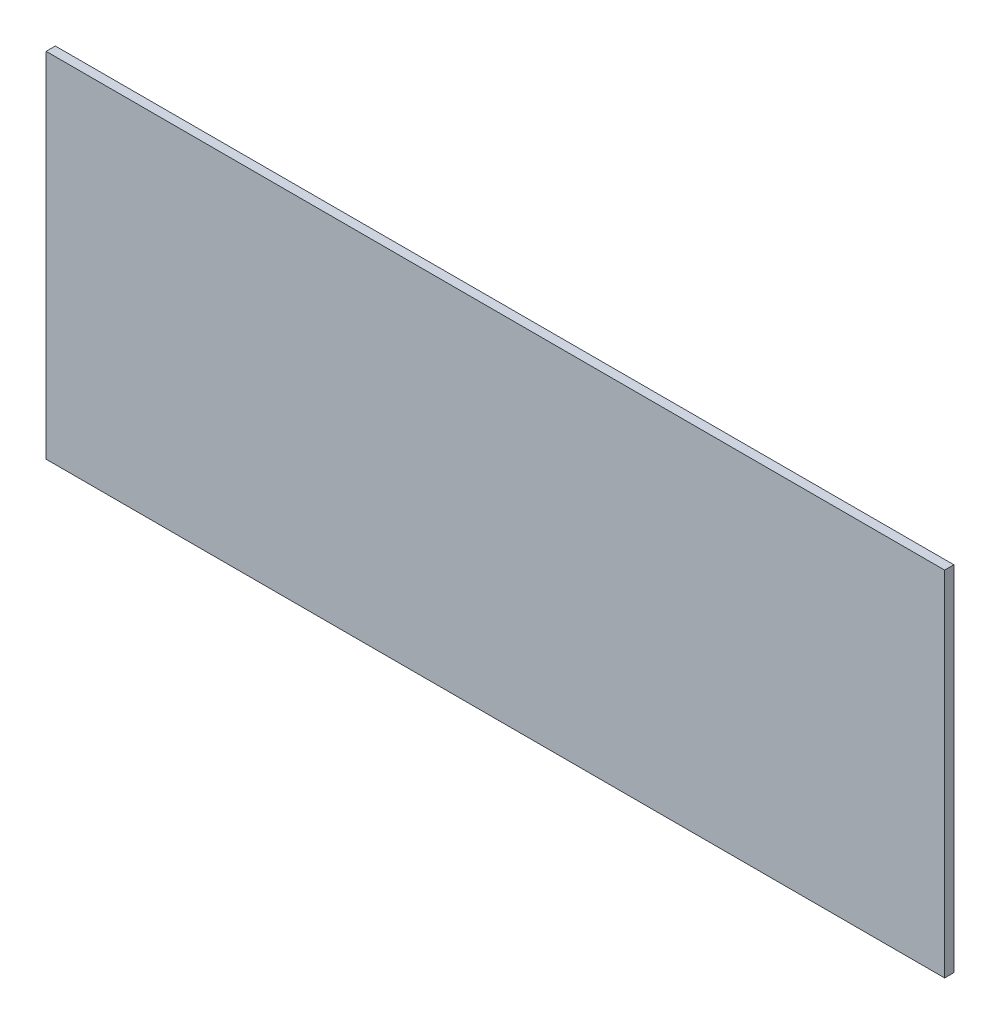
SolidWorks part; units mm, degrees
ref_plane "Front Plane" through (0, 0, 0) normal (0, 0, 1) x (1, 0, 0)
ref_plane "Top Plane" through (0, 0, 0) normal (0, 1, 0) x (1, 0, 0)
ref_plane "Right Plane" through (0, 0, 0) normal (1, 0, 0) x (0, 0, -1)
ref_plane "Plane1" through (0, 0, 0) normal (0, 0, -1) x (-1, 0, 0)
sketch "Sketch1" plane through (0, 0, 0) normal (0, 0, -1) x (-1, 0, 0)
  line L0 (-146, 57.4) -> (-146, -57.4)
  line L1 (-146, -57.4) -> (146, -57.4)
  line L2 (146, -57.4) -> (146, 57.4)
  line L3 (146, 57.4) -> (-146, 57.4)
extrude "Boss-Extrude1" add sketch "Sketch1" against normal blind 3
